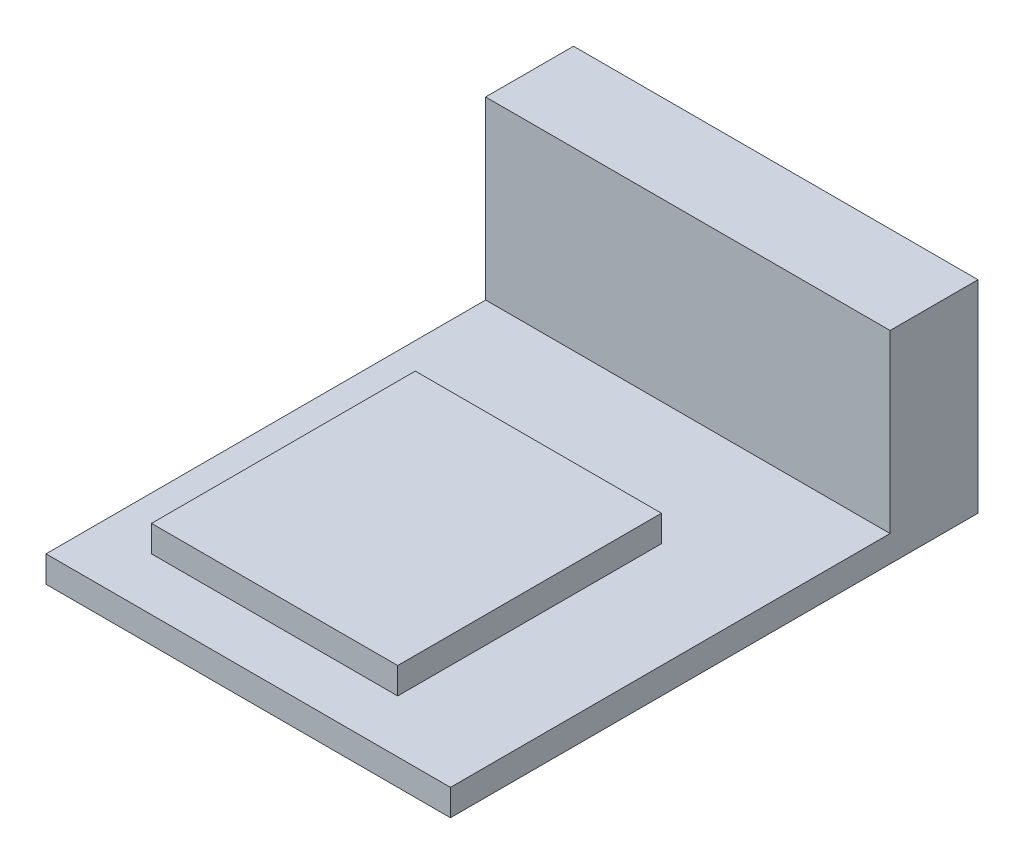
SolidWorks part; units mm, degrees
other "Исправление3"
sketch "Эскиз6" plane through (23, 3, 30) normal (0.5061, 0.739, 0.4446) x (0.6964, -0.0461, -0.7162)
ref_plane "Спереди" through (0, 0, 0) normal (0, 0, 1) x (1, 0, 0)
ref_plane "Сверху" through (0, 0, 0) normal (0, 1, 0) x (1, 0, 0)
ref_plane "Справа" through (0, 0, 0) normal (1, 0, 0) x (0, 0, -1)
other "Configuration Table"
sketch "Эскиз1" plane through (0, 0, 0) normal (0, 1, 0) x (1, 0, 0)
  line L1 (0, 0) -> (23, 0)
  line L2 (0, 0) -> (0, -30)
  line L3 (0, -30) -> (23, -30)
  line L4 (23, 0) -> (23, -30)
  dimension "D1" = 23
  dimension "D2" = 30
extrude "Бобышка-Вытянуть1" add sketch "Эскиз1" along normal blind 1.5
sketch "Эскиз2" plane through (0, 1.5, 0) normal (0, 1, 0) x (1, 0, 0)
  line L0 (23, -30) -> (23, 0) construction
  line L1 (3, -12) -> (17, -12)
  line L2 (3, -12) -> (3, -27)
  line L3 (3, -27) -> (17, -27)
  line L4 (17, -12) -> (17, -27)
  line L5 (0, 0) -> (0, -30) construction
  line L6 (0, -30) -> (23, -30) construction
  dimension "D1" = 6
  dimension "D2" = 3
  dimension "D3" = 15
  dimension "D4" = 3
extrude "Бобышка-Вытянуть2" add sketch "Эскиз2" along normal blind 1.5
sketch "Эскиз3" plane through (0, 1.5, 0) normal (0, 1, 0) x (1, 0, 0)
  line L0 (23, -30) -> (23, 0) construction
  line L1 (0, 0) -> (23, 0)
  line L2 (0, 0) -> (0, -5)
  line L3 (0, -5) -> (23, -5)
  line L4 (23, 0) -> (23, -5)
  dimension "D1" = 5
extrude "Бобышка-Вытянуть3" add sketch "Эскиз3" along normal blind 10 contours L2 L1 L4 L3
